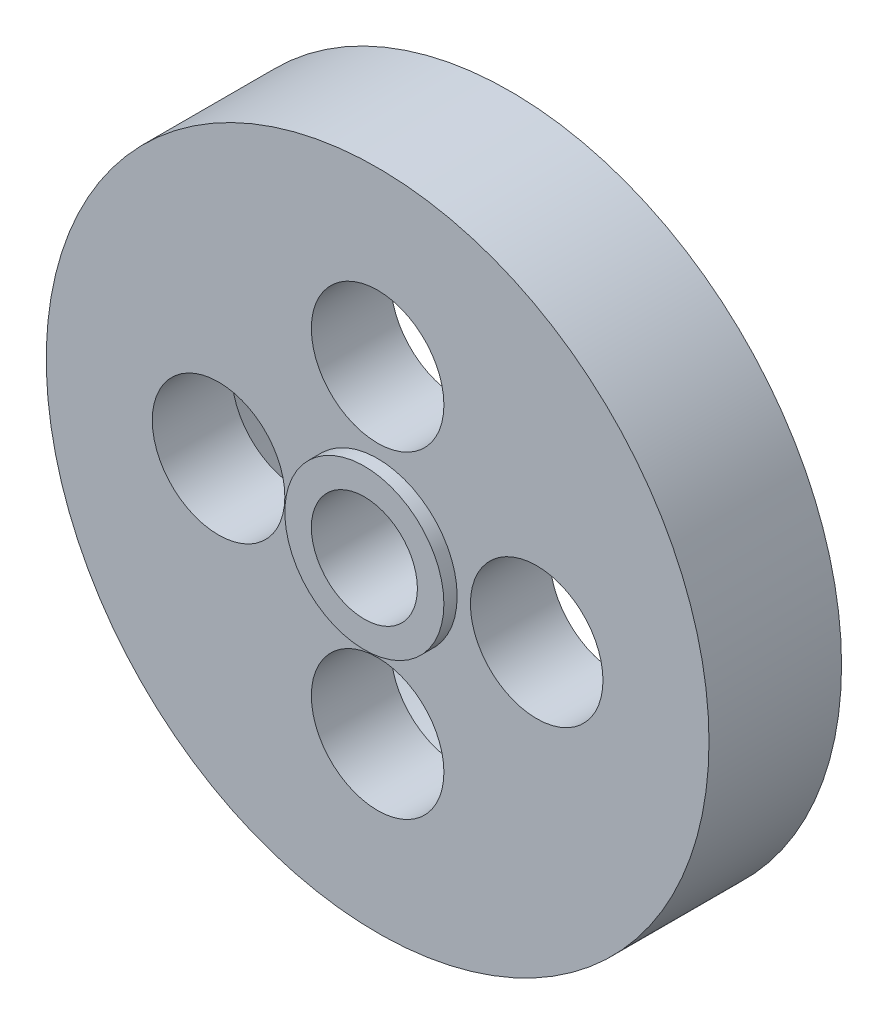
SolidWorks part; units mm, degrees
ref_plane "Front Plane" through (0, 0, 0) normal (0, 0, 1) x (1, 0, 0)
ref_plane "Top Plane" through (0, 0, 0) normal (0, 1, 0) x (1, 0, 0)
ref_plane "Right Plane" through (0, 0, 0) normal (1, 0, 0) x (0, 0, -1)
sketch "Sketch2" plane through (0, 0, 0) normal (0, 0, 1) x (1, 0, 0)
  circle A0 centre (0, 0) radius 25
  circle A1 centre (0, 0) radius 12 construction
  circle A2 centre (0, 12) radius 5
  circle A3 centre (0, 0) radius 4
  circle A4 centre (12, 0) radius 5
  circle A5 centre (0, -12) radius 5
  circle A6 centre (-12, 0) radius 5
  point P16 (0, 0)
  dimension "D1" = 10
  dimension "D2" = 50
  dimension "D3" = 24
  dimension "D4" = 8
  dimension "D5" = 4
extrude "Boss-Extrude1" add sketch "Sketch2" along normal mid plane 10
sketch "Sketch3" plane through (0, 0, -5) normal (0, 0, -1) x (-1, 0, 0)
  circle A0 centre (0, 0) radius 18
  dimension "D1" = 36
extrude "Cut-Extrude1" cut sketch "Sketch3" against normal blind 4
sketch "Sketch5" plane through (0, 0, 5) normal (0, 0, 1) x (1, 0, 0)
  circle A0 centre (0, 0) radius 4
  circle A1 centre (0, 0) radius 6
  dimension "D1" = 12
  dimension "D2" = 8
extrude "Boss-Extrude2" add sketch "Sketch5" along normal blind 1
